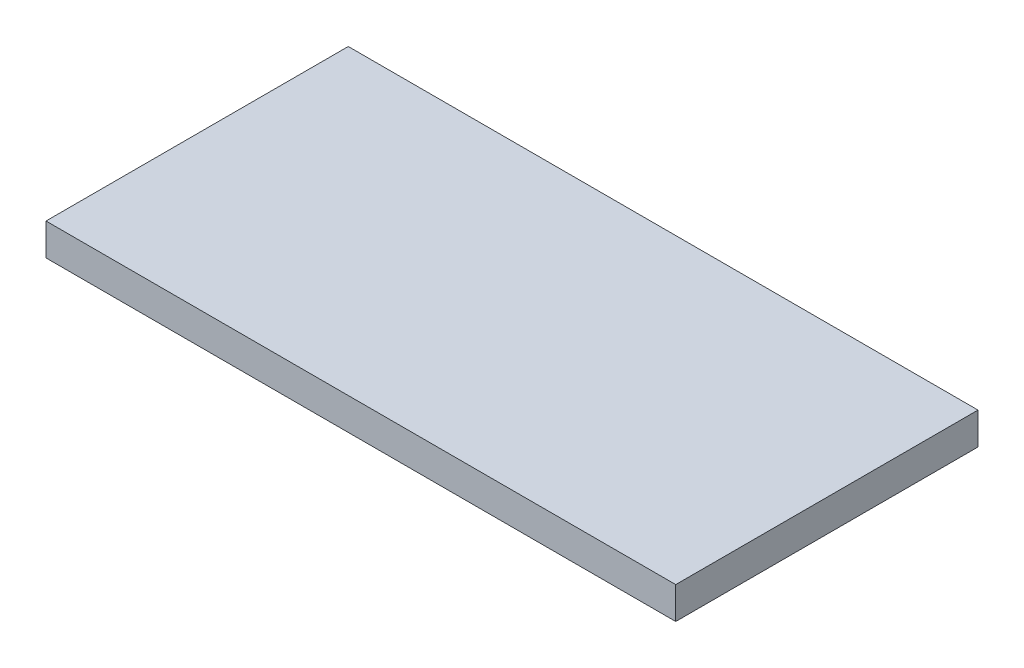
SolidWorks part; units mm, degrees
material "Pine"
ref_plane "Front Plane" through (0, 0, 0) normal (0, 0, 1) x (1, 0, 0)
ref_plane "Top Plane" through (0, 0, 0) normal (0, 1, 0) x (1, 0, 0)
ref_plane "Right Plane" through (0, 0, 0) normal (1, 0, 0) x (0, 0, -1)
sketch "Sketch2" plane through (0, 0, 0) normal (0, 1, 0) x (1, 0, 0)
  line L1 (-187.5, 90) -> (187.5, 90)
  line L2 (-187.5, 90) -> (-187.5, -90)
  line L3 (-187.5, -90) -> (187.5, -90)
  line L4 (187.5, 90) -> (187.5, -90)
  line L5 (-187.5, 90) -> (187.5, -90) construction
  line L6 (-187.5, -90) -> (187.5, 90) construction
  point P0 (0, 0)
  dimension "D1" = 375
  dimension "D2" = 180
extrude "Boss-Extrude1" add sketch "Sketch2" along normal blind 19.05
